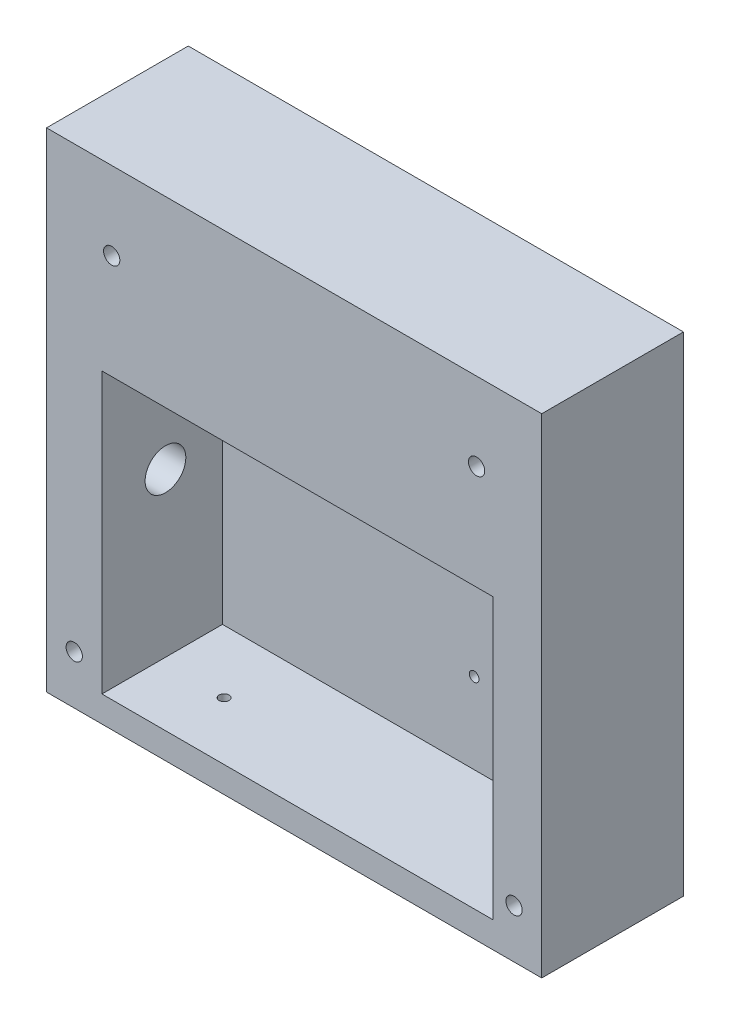
SolidWorks part; units mm, degrees
ref_plane "Front Plane" through (0, 0, 0) normal (0, 0, 1) x (1, 0, 0)
ref_plane "Top Plane" through (0, 0, 0) normal (0, 1, 0) x (1, 0, 0)
ref_plane "Right Plane" through (0, 0, 0) normal (1, 0, 0) x (0, 0, -1)
sketch "Sketch1" plane through (0, 0, 0) normal (0, 0, 1) x (1, 0, 0)
  line L1 (0, 0) -> (152, 0)
  line L2 (0, 0) -> (0, 150)
  line L3 (0, 150) -> (152, 150)
  line L4 (152, 0) -> (152, 150)
  dimension "D1" = 150
  dimension "D2" = 152
extrude "Boss-Extrude1" add sketch "Sketch1" along normal blind 6.5
sketch "Sketch2" plane through (0, 0, 6.5) normal (0, 0, 1) x (1, 0, 0)
  line L0 (152, 0) -> (152, 150) construction
  line L1 (0, 0) -> (152, 0)
  line L2 (0, 0) -> (0, 8)
  line L3 (0, 8) -> (152, 8)
  line L4 (152, 0) -> (152, 8)
  dimension "D1" = 8
  dimension "D2" = 152
extrude "Boss-Extrude2" add sketch "Sketch2" along normal blind 37
sketch "Sketch3" plane through (0, 0, 6.5) normal (0, 0, 1) x (1, 0, 0)
  line L0 (152, 150) -> (0, 150) construction
  line L1 (0, 8) -> (17, 8)
  line L2 (0, 8) -> (0, 150)
  line L3 (0, 150) -> (17, 150)
  line L4 (17, 8) -> (17, 150)
  dimension "D1" = 17
extrude "Boss-Extrude3" add sketch "Sketch3" along normal up to vertex (37 mm away)
sketch "Sketch4" plane through (0, 0, 6.5) normal (0, 0, 1) x (1, 0, 0)
  line L0 (152, 150) -> (17, 150) construction
  line L1 (152, 8) -> (137, 8)
  line L2 (152, 8) -> (152, 150)
  line L3 (152, 150) -> (137, 150)
  line L4 (137, 8) -> (137, 150)
  dimension "D1" = 15
extrude "Boss-Extrude4" add sketch "Sketch4" along normal blind 37
sketch "Sketch5" plane through (0, 0, 6.5) normal (0, 0, 1) x (1, 0, 0)
  line L0 (137, 150) -> (137, 8) construction
  line L1 (17, 150) -> (137, 150)
  line L2 (17, 150) -> (17, 93.88)
  line L3 (17, 93.88) -> (137, 93.88)
  line L4 (137, 150) -> (137, 93.88)
  dimension "D1" = 56.12
extrude "Boss-Extrude5" add sketch "Sketch5" along normal blind 37
sketch "Sketch6" plane through (0, 8, 0) normal (0, 1, 0) x (1, 0, 0)
  line L0 (137, -43.5) -> (137, -6.5) construction
  line L1 (137, -43.5) -> (17, -43.5) construction
  point P0 (36.75, -25.75)
  dimension "D1" = 100.25
  dimension "D2" = 17.75
sketch "Sketch7" plane through (0, 0, 0) normal (0, -1, 0) x (1, 0, 0)
  point P0 (36.75, 25.75)
hole_wizard "Hole2" positions "3DSketch2" profile "Sketch11" legacy
sketch3d "3DSketch2"
  point P0 (36.75, 0, 25.75)
sketch "Sketch11" plane through (36.75, 0, 25.75) normal (1, 0, 0) x (0, 0, -1)
  line L0 (0, 0) -> (0, 8)
  line L1 (0, 8) -> (1.5, 8)
  line L2 (1.5, 8) -> (1.5, 4.5)
  line L3 (1.5, 4.5) -> (3, 4.5)
  line L4 (3, 4.5) -> (3, 0)
  line L5 (3, 0) -> (0, 0)
  line L6 (0, 110) -> (0, -10) construction
  dimension "Diameter" = 3
  dimension "Depth" = 8
  dimension "C-Bore Diameter" = 6
  dimension "C-Bore Depth" = 4.5
sketch "Sketch12" plane through (0, 8, 0) normal (0, 1, 0) x (1, 0, 0)
  line L0 (137, -43.5) -> (137, -6.5) construction
  line L1 (137, -43.5) -> (17, -43.5) construction
  point P0 (124.25, -19.75)
  dimension "D1" = 12.75
  dimension "D2" = 23.75
sketch "Sketch13" plane through (0, 0, 0) normal (0, -1, 0) x (1, 0, 0)
  point P0 (124.25, 19.75)
hole_wizard "Hole3" positions "3DSketch3" profile "Sketch15" legacy
sketch3d "3DSketch3"
  point P0 (124.25, 0, 19.75)
sketch "Sketch15" plane through (124.25, 0, 19.75) normal (1, 0, 0) x (0, 0, -1)
  line L0 (0, 0) -> (0, 8)
  line L1 (0, 8) -> (1.5, 8)
  line L2 (1.5, 8) -> (1.5, 4.5)
  line L3 (1.5, 4.5) -> (3, 4.5)
  line L4 (3, 4.5) -> (3, 0)
  line L5 (3, 0) -> (0, 0)
  line L6 (0, 110) -> (0, -10) construction
  dimension "Diameter" = 3
  dimension "Depth" = 8
  dimension "C-Bore Diameter" = 6
  dimension "C-Bore Depth" = 4.5
sketch "Sketch16" plane through (17, 0, 0) normal (1, 0, 0) x (0, 0, -1)
  line L0 (-43.5, 8) -> (-6.5, 8) construction
  line L1 (-6.5, 8) -> (-6.5, 93.88) construction
  point P0 (-24, 58)
  dimension "D1" = 50
  dimension "D2" = 17.5
hole_wizard "Hole4" positions "3DSketch4" profile "Sketch19" legacy
sketch3d "3DSketch4"
  point P0 (17, 58, 24)
sketch "Sketch19" plane through (17, 58, 24) normal (0, 1, 0) x (0, 0, -1)
  line L0 (0, 0) -> (0, 17)
  line L1 (0, 17) -> (6.25, 17)
  line L2 (6.25, 17) -> (6.25, 0)
  line L3 (6.25, 0) -> (0, 0)
  line L4 (0, 110) -> (0, -10) construction
  dimension "Diameter" = 12.5
  dimension "Depth" = 17
sketch "Sketch20" plane through (0, 0, 6.5) normal (0, 0, 1) x (1, 0, 0)
  line L0 (137, 8) -> (17, 8) construction
  line L1 (137, 93.88) -> (137, 8) construction
  point P0 (94.25, 32.75)
  dimension "D1" = 24.75
  dimension "D2" = 42.75
sketch "Sketch21" plane through (0, 0, 0) normal (0, 0, -1) x (-1, 0, 0)
  point P0 (-94.25, 32.75)
hole_wizard "Hole5" positions "3DSketch5" profile "Sketch23" legacy end condition up to next
sketch3d "3DSketch5"
  point P0 (94.25, 32.75, 0)
sketch "Sketch23" plane through (94.25, 32.75, 0) normal (1, 0, 0) x (0, 1, 0)
  line L0 (0, 0) -> (0, 6.5)
  line L1 (0, 6.5) -> (1.5, 6.5)
  line L2 (1.5, 6.5) -> (1.5, 4)
  line L3 (1.5, 4) -> (3, 4)
  line L4 (3, 4) -> (3, 0)
  line L5 (3, 0) -> (0, 0)
  line L6 (0, 110) -> (0, -10) construction
  dimension "Diameter" = 3
  dimension "Depth" = 6.5
  dimension "C-Bore Diameter" = 6
  dimension "C-Bore Depth" = 4
sketch "Sketch24" plane through (0, 0, 6.5) normal (0, 0, 1) x (1, 0, 0)
  line L0 (137, 8) -> (17, 8) construction
  line L1 (137, 93.88) -> (137, 8) construction
  point P0 (94.25, 60.75)
  dimension "D1" = 52.75
  dimension "D2" = 42.75
sketch "Sketch25" plane through (0, 0, 0) normal (0, 0, -1) x (-1, 0, 0)
  point P0 (-94.25, 60.75)
hole_wizard "Hole6" positions "3DSketch6" profile "Sketch27" legacy end condition up to next
sketch3d "3DSketch6"
  point P0 (94.25, 60.75, 0)
sketch "Sketch27" plane through (94.25, 60.75, 0) normal (1, 0, 0) x (0, 1, 0)
  line L0 (0, 0) -> (0, 6.5)
  line L1 (0, 6.5) -> (1.5, 6.5)
  line L2 (1.5, 6.5) -> (1.5, 4)
  line L3 (1.5, 4) -> (3, 4)
  line L4 (3, 4) -> (3, 0)
  line L5 (3, 0) -> (0, 0)
  line L6 (0, 110) -> (0, -10) construction
  dimension "Diameter" = 3
  dimension "Depth" = 6.5
  dimension "C-Bore Diameter" = 6
  dimension "C-Bore Depth" = 4
sketch "Sketch28" plane through (0, 0, 6.5) normal (0, 0, 1) x (1, 0, 0)
  line L0 (137, 8) -> (17, 8) construction
  circle A0 centre (94.25, 60.75) radius 1.5 construction
  point P0 (59, 60.75)
  dimension "D1" = 52.75
  dimension "D2" = 35.25
sketch "Sketch31" plane through (0, 0, 0) normal (0, 0, -1) x (-1, 0, 0)
  point P0 (-59, 60.75)
hole_wizard "Hole7" positions "3DSketch8" profile "Sketch33" legacy end condition up to next
sketch3d "3DSketch8"
  point P0 (59, 60.75, 0)
sketch "Sketch33" plane through (59, 60.75, 0) normal (1, 0, 0) x (0, 1, 0)
  line L0 (0, 0) -> (0, 6.5)
  line L1 (0, 6.5) -> (1.5, 6.5)
  line L2 (1.5, 6.5) -> (1.5, 4)
  line L3 (1.5, 4) -> (3, 4)
  line L4 (3, 4) -> (3, 0)
  line L5 (3, 0) -> (0, 0)
  line L6 (0, 110) -> (0, -10) construction
  dimension "Diameter" = 3
  dimension "Depth" = 6.5
  dimension "C-Bore Diameter" = 6
  dimension "C-Bore Depth" = 4
sketch "Sketch34" plane through (0, 0, 0) normal (0, 0, -1) x (-1, 0, 0)
  line L1 (-152, 150) -> (-132, 150)
  line L2 (-152, 150) -> (-152, 126)
  line L3 (-152, 126) -> (-132, 126)
  line L4 (-132, 150) -> (-132, 126)
  line L5 (0, 150) -> (-20, 150)
  line L6 (0, 150) -> (0, 126)
  line L7 (0, 126) -> (-20, 126)
  line L8 (-20, 150) -> (-20, 126)
  dimension "D1" = 20
  dimension "D2" = 24
  dimension "D3" = 20
  dimension "D4" = 24
hole_wizard "Hole9" positions "3DSketch10" profile "Sketch38" legacy end condition up to next
sketch3d "3DSketch10"
  point P0 (132, 126, 0)
  point P3 (20, 126, 0)
sketch "Sketch38" plane through (132, 126, 0) normal (1, 0, 0) x (0, 1, 0)
  line L0 (0, 0) -> (0, 43.5)
  line L1 (0, 43.5) -> (2.5, 43.5)
  line L2 (2.5, 43.5) -> (2.5, 23.5)
  line L3 (2.5, 23.5) -> (5, 23.5)
  line L4 (5, 23.5) -> (5, 0)
  line L5 (5, 0) -> (0, 0)
  line L6 (0, 110) -> (0, -10) construction
  dimension "Diameter" = 5
  dimension "Depth" = 43.5
  dimension "C-Bore Diameter" = 10
  dimension "C-Bore Depth" = 23.5
sketch "Sketch39" plane through (0, 0, 0) normal (0, 0, -1) x (-1, 0, 0)
  line L1 (0, 0) -> (-8.5, 0)
  line L2 (0, 0) -> (0, 15)
  line L3 (0, 15) -> (-8.5, 15)
  line L4 (-8.5, 0) -> (-8.5, 15)
  line L5 (-152, 0) -> (-143.5, 0)
  line L6 (-152, 0) -> (-152, 15)
  line L7 (-152, 15) -> (-143.5, 15)
  line L8 (-143.5, 0) -> (-143.5, 15)
  dimension "D1" = 8.5
  dimension "D2" = 8.5
  dimension "D3" = 15
  dimension "D4" = 15
hole_wizard "Hole10" positions "3DSketch11" profile "Sketch41" legacy
sketch3d "3DSketch11"
  point P0 (143.5, 15, 0)
  point P3 (8.5, 15, 0)
sketch "Sketch41" plane through (143.5, 15, 0) normal (1, 0, 0) x (0, 1, 0)
  line L0 (0, 0) -> (0, 43.5)
  line L1 (0, 43.5) -> (2.5, 43.5)
  line L2 (2.5, 43.5) -> (2.5, 23.5)
  line L3 (2.5, 23.5) -> (5, 23.5)
  line L4 (5, 23.5) -> (5, 0)
  line L5 (5, 0) -> (0, 0)
  line L6 (0, 110) -> (0, -10) construction
  dimension "Diameter" = 5
  dimension "Depth" = 43.5
  dimension "C-Bore Diameter" = 10
  dimension "C-Bore Depth" = 23.5
